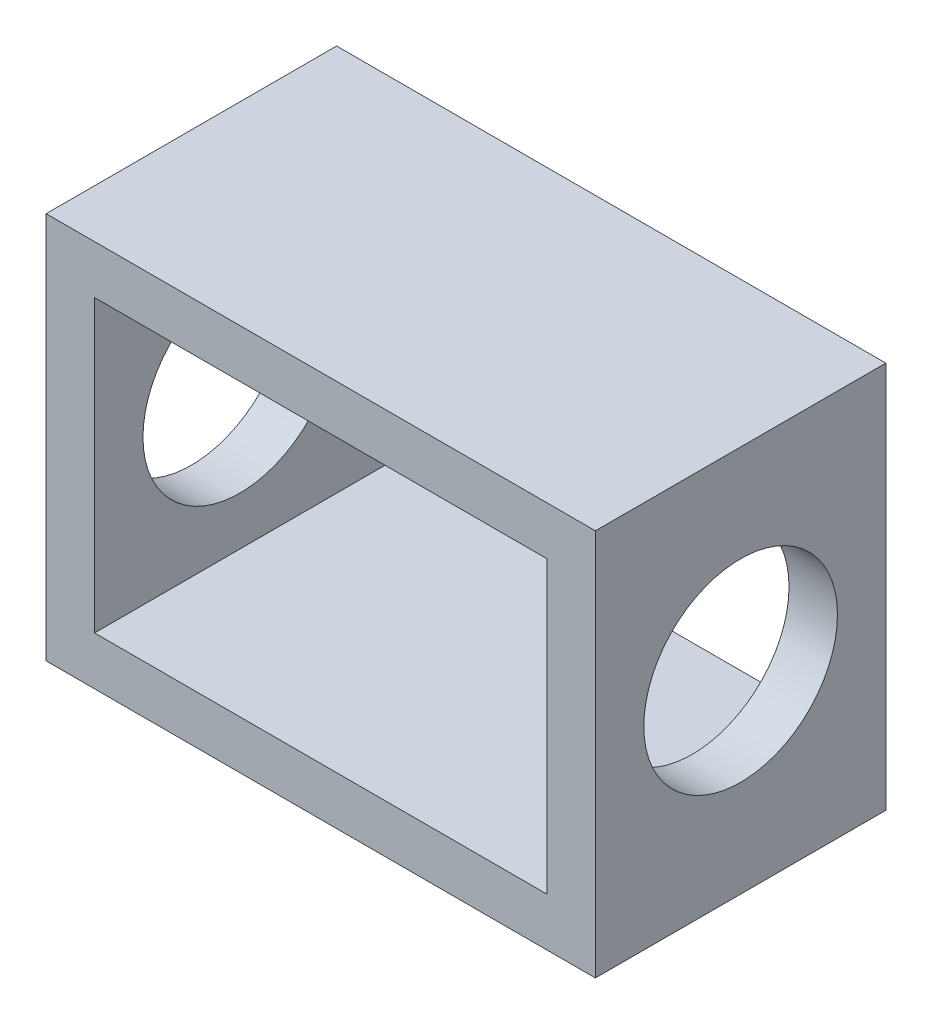
SolidWorks part; units mm, degrees
ref_plane "Front Plane" through (0, 0, 0) normal (0, 0, 1) x (1, 0, 0)
ref_plane "Top Plane" through (0, 0, 0) normal (0, 1, 0) x (1, 0, 0)
ref_plane "Right Plane" through (0, 0, 0) normal (1, 0, 0) x (0, 0, -1)
sketch "Sketch1" plane through (0, 0, 0) normal (0, 0, 1) x (1, 0, 0)
  line L1 (-25.8648, 17.5) -> (25.8648, 17.5)
  line L2 (-25.8648, 17.5) -> (-25.8648, -17.5)
  line L3 (-25.8648, -17.5) -> (25.8648, -17.5)
  line L4 (25.8648, 17.5) -> (25.8648, -17.5)
  line L5 (-25.8648, 17.5) -> (25.8648, -17.5) construction
  line L6 (-25.8648, -17.5) -> (25.8648, 17.5) construction
  point P0 (0, 0)
  dimension "D1" = 35
extrude "Extrude-Thin1" add sketch "Sketch1" along normal blind 30 thin thin type mid plane wall 5
sketch "Sketch2" plane through (-28.3648, 0, 0) normal (-1, 0, 0) x (0, 0, 1)
  line L0 (0, 0) -> (33.8447, 0) construction
  line L2 (0, 20) -> (0, -20) construction
  circle A0 centre (15, 0) radius 10
  dimension "D1" = 15
extrude "Cut-Extrude1" cut sketch "Sketch2" against normal through all
